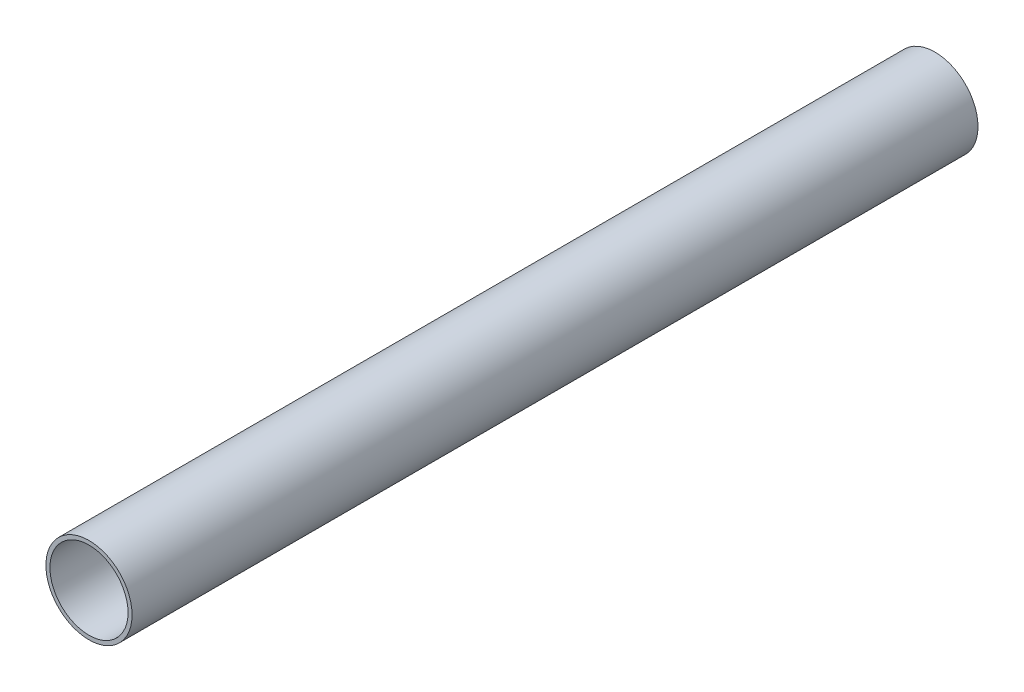
SolidWorks part; units mm, degrees
ref_plane "Alzado" through (0, 0, 0) normal (0, 0, 1) x (1, 0, 0)
ref_plane "Planta" through (0, 0, 0) normal (0, 1, 0) x (1, 0, 0)
ref_plane "Vista lateral" through (0, 0, 0) normal (1, 0, 0) x (0, 0, -1)
sketch "Croquis1" plane through (0, 0, 0) normal (0, 0, 1) x (1, 0, 0)
  circle A0 centre (0, 0) radius 12.7
  circle A1 centre (0, 0) radius 14
  dimension "D1" = 25.4
  dimension "D2" = 28
extrude "Saliente-Extruir1" add sketch "Croquis1" along normal blind 275
